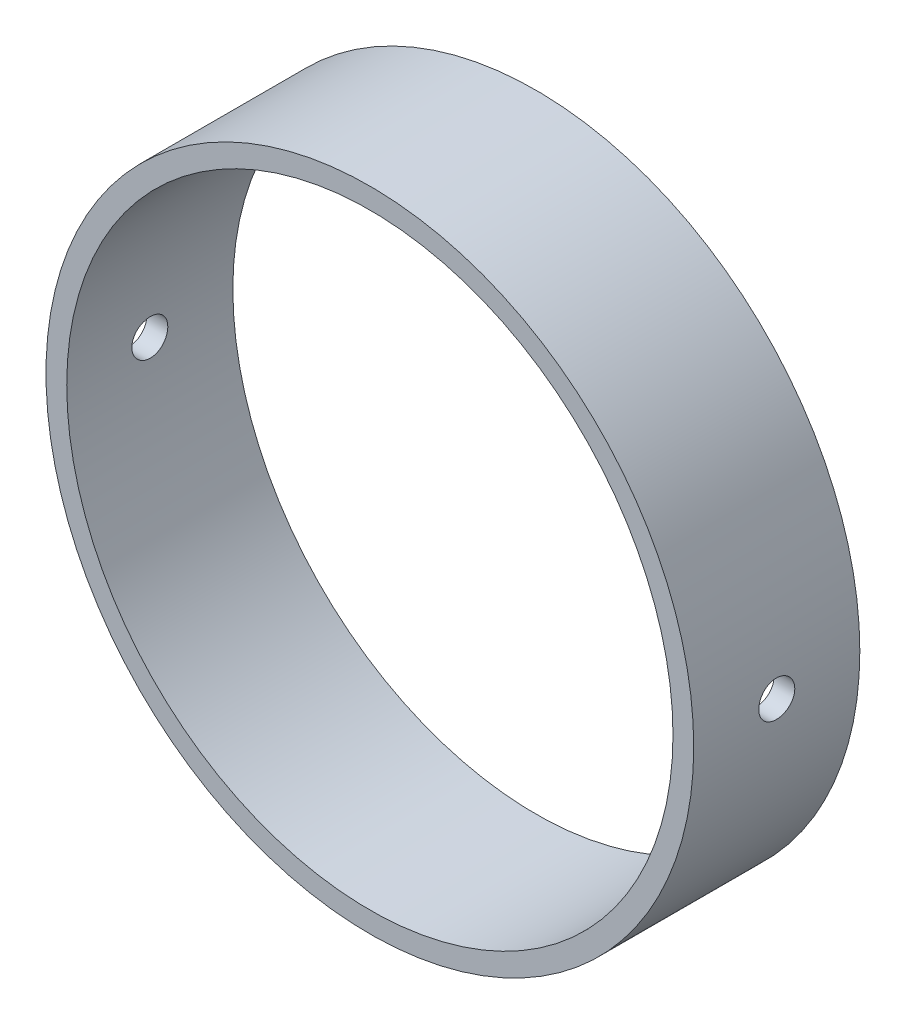
SolidWorks part; units mm, degrees
material "Galvanized Steel"
ref_plane "Front Plane" through (0, 0, 0) normal (0, 0, 1) x (1, 0, 0)
ref_plane "Top Plane" through (0, 0, 0) normal (0, 1, 0) x (1, 0, 0)
ref_plane "Right Plane" through (0, 0, 0) normal (1, 0, 0) x (0, 0, -1)
sketch "Sketch1" plane through (0, 0, 0) normal (0, 0, 1) x (1, 0, 0)
  circle A0 centre (0, 0) radius 58.5
  circle A1 centre (0, 0) radius 54.75
  dimension "D1" = 117
  dimension "D2" = 109.5
extrude "Boss-Extrude1" add sketch "Sketch1" along normal blind 30
sketch "Sketch2" plane through (0, 0, 0) normal (1, 0, 0) x (0, 0, -1)
  circle A0 centre (-15, 0) radius 3.25
  dimension "D1" = 6.5
extrude "Cut-Extrude1" cut sketch "Sketch2" against normal through all both and the other way through all
